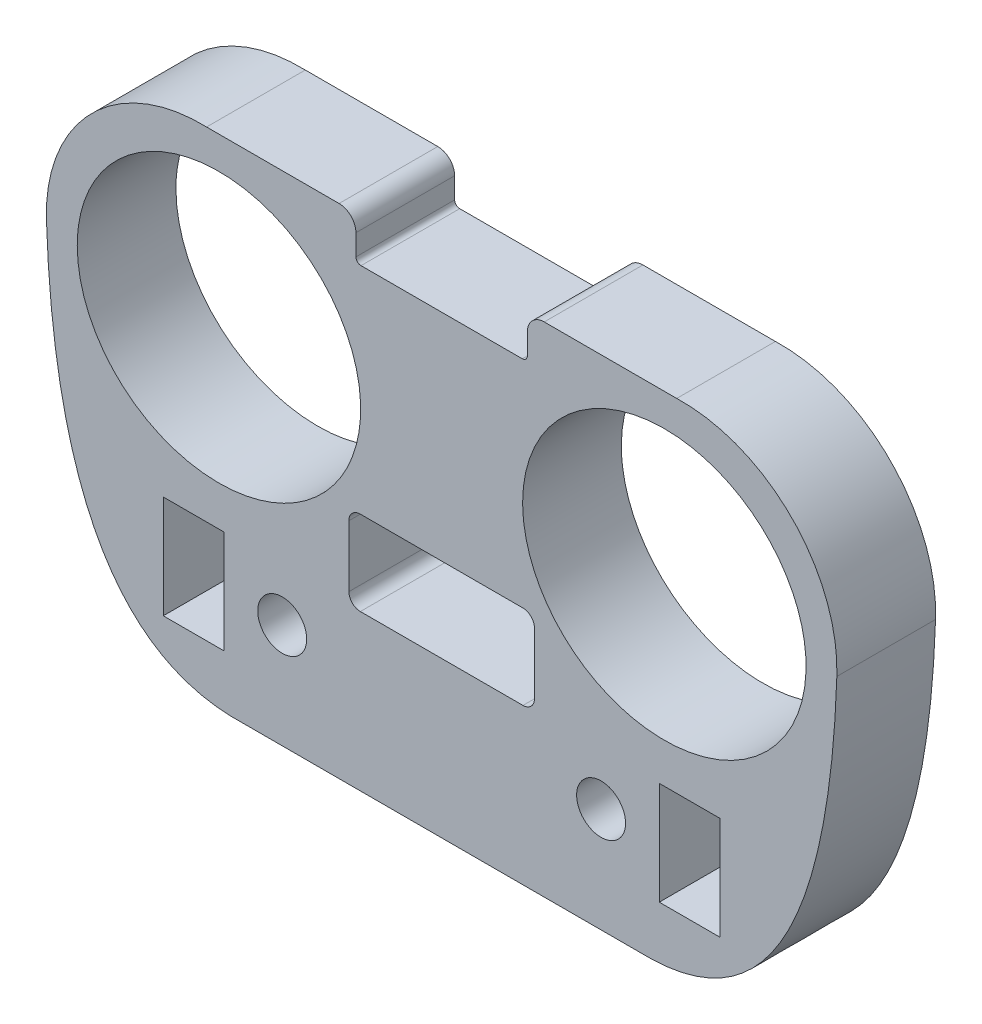
SolidWorks part; units mm, degrees
material "Acrylic (Medium-high impact)"
ref_plane "Front Plane" through (0, 0, 0) normal (0, 0, 1) x (1, 0, 0)
ref_plane "Top Plane" through (0, 0, 0) normal (0, 1, 0) x (1, 0, 0)
ref_plane "Right Plane" through (0, 0, 0) normal (1, 0, 0) x (0, 0, -1)
sketch "Model" plane through (0, 0, 0) normal (0, 0, 1) x (1, 0, 0)
  line L0 (549.8561, 574.3347) -> (554.6761, 574.3347)
  line L1 (554.6761, 576.8347) -> (549.1761, 576.8347) construction
  line L2 (554.6761, 576.8347) -> (560.1761, 576.8347) construction
  line L3 (554.6761, -405.4445) -> (554.6761, 49594.5555) construction
  line L4 (540.7427, 594.6497) -> (549.5961, 594.6497)
  line L5 (542.1922, 565.1247) -> (567.16, 565.1247)
  line L6 (549.8561, 579.3347) -> (554.6761, 579.3347)
  line L7 (567.5761, 574.3747) -> (567.5761, 568.2747)
  line L8 (571.1761, 574.3747) -> (567.5761, 574.3747)
  line L9 (571.1761, 568.2747) -> (571.1761, 574.3747)
  line L10 (567.5761, 568.2747) -> (571.1761, 568.2747)
  line L11 (560.1761, 578.6547) -> (560.1761, 575.0147)
  line L12 (559.4961, 579.3347) -> (554.6761, 579.3347)
  line L13 (559.4961, 574.3347) -> (554.6761, 574.3347)
  line L14 (538.7761, 571.3247) -> (570.5761, 571.3247) construction
  line L15 (541.4761, 584.7347) -> (567.8761, 584.7347) construction
  line L16 (549.5961, 592.1097) -> (559.7561, 592.1097)
  line L17 (549.5961, 592.1097) -> (549.5961, 594.6497)
  line L18 (559.7561, 592.1097) -> (559.7561, 594.6497)
  line L19 (559.7561, 594.6497) -> (568.6095, 594.6497)
  line L20 (541.4761, 584.7347) -> (541.4761, 592.7347) construction
  line L21 (549.1761, 578.6547) -> (549.1761, 575.0147)
  line L32 (541.7761, 568.2747) -> (538.1761, 568.2747)
  line L33 (538.1761, 568.2747) -> (538.1761, 574.3747)
  line L34 (538.1761, 574.3747) -> (541.7761, 574.3747)
  line L35 (541.7761, 574.3747) -> (541.7761, 568.2747)
  circle A0 centre (545.2261, 571.3247) radius 1.45
  arc A1 (578.1008, 585.1247) -> (568.6095, 594.6497) centre (568.8929, 585.4407) ccw
  arc A3 (549.1761, 575.0147) -> (549.8561, 574.3347) centre (549.8561, 575.0147) ccw
  arc A4 (549.1761, 578.6547) -> (549.8561, 579.3347) centre (549.8561, 578.6547) cw
  arc A5 (560.1761, 578.6547) -> (559.4961, 579.3347) centre (559.4961, 578.6547) ccw
  arc A6 (560.1761, 575.0147) -> (559.4961, 574.3347) centre (559.4961, 575.0147) cw
  arc A7 (531.2514, 585.1247) -> (540.7427, 594.6497) centre (540.4593, 585.4407) cw
  circle A9 centre (564.1261, 571.3247) radius 1.45
  ellipse E0 centre (541.4761, 584.7347) end of major axis (533.0761, 584.7347) minor radius 8
  ellipse E1 centre (567.8761, 584.7347) end of major axis (559.4761, 584.7347) minor radius 8
  spline S0 degree 2 poles (578.1008, 585.1247) (577.4253, 565.4445) (567.16, 565.1247) knots 0 0 0 1 1 1
  spline S48 degree 2 poles (531.2514, 585.1247) (531.9269, 565.4445) (542.1922, 565.1247) knots 0 0 0 1 1 1
  point P0 (554.6761, 571.3247)
  point P2 (541.4761, 592.7347)
  point P19 (549.8761, 584.7347)
  point P32 (559.4761, 584.7347)
  point P33 (554.6761, 584.7347)
  point P34 (554.6761, 565.1247)
  point P36 (554.6761, 576.8347)
  point P40 (554.6761, 592.1097)
  dimension "D11" = 2.9
  dimension "D12" = 8
  dimension "D14" = 0.68
  dimension "D16" = 10.16
  dimension "D1" = 3.45
  dimension "D2" = 9.45
  dimension "D3" = 20
  dimension "D4" = 6.1
  dimension "D5" = 11
  dimension "D6" = 5
  dimension "D7" = 3.6
  dimension "D8" = 29.525
  dimension "D9" = 6.2
  dimension "D10" = 0.04
  dimension "D13" = 13.2
  dimension "D15" = 7.9
  dimension "D17" = 2.54
  dimension "D18" = 5.51
  dimension "D19" = 8.4
extrude "Boss-Extrude1" add sketch "Model" along normal blind 5.85 contours A7 S48 L5 S0 A1 L4 A9 L11 A6 L13 L0 A3 L21 A4 L6 L12 A5 E0 A0 L10 L7 L8 L9 L34 L35 L32 L33 E1
fillet "Fillet1" radius 0.3 2 edges at (559.7561, 592.1097, 2.925) (549.5961, 592.1097, 2.925)
fillet "Fillet2" radius 1 2 edges at (559.7561, 594.6497, 2.925) (549.5961, 594.6497, 2.925)
